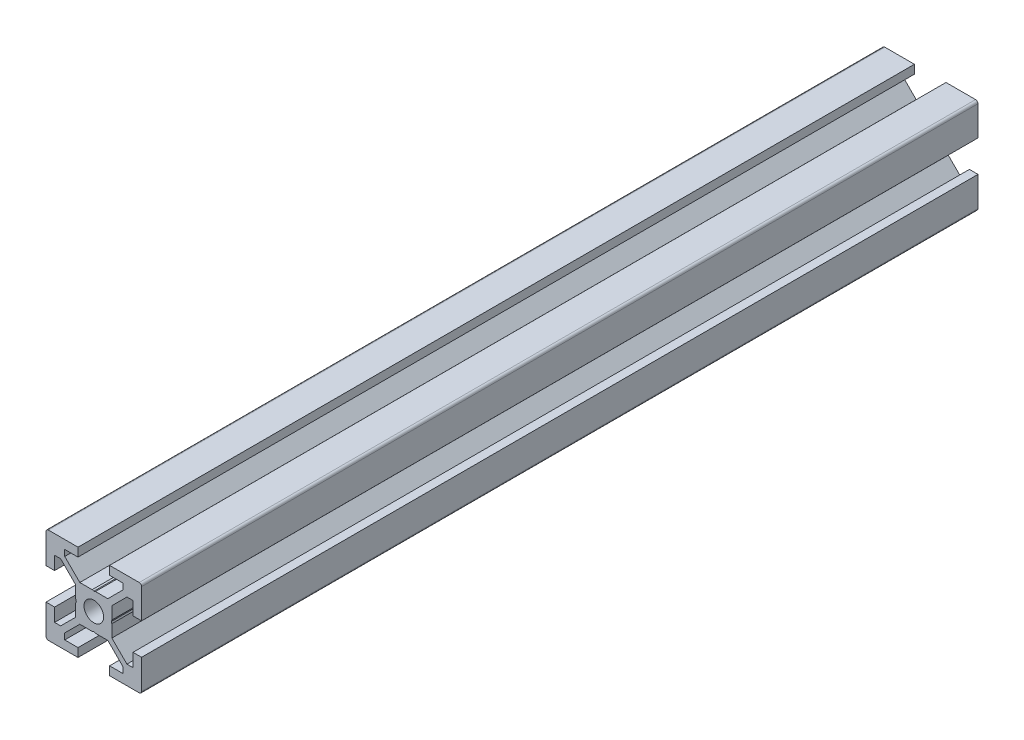
SolidWorks part; units mm, degrees
ref_plane "Front Plane" through (0, 0, 0) normal (0, 0, 1) x (1, 0, 0)
ref_plane "Top Plane" through (0, 0, 0) normal (0, 1, 0) x (1, 0, 0)
ref_plane "Right Plane" through (0, 0, 0) normal (1, 0, 0) x (0, 0, -1)
sketch "Sketch1" plane through (0, 0, 0) normal (0, 0, 1) x (1, 0, 0)
  line L0 (-3.3, 10) -> (-3.3, 8.2)
  line L1 (0, 0) -> (50000, 0) construction
  line L2 (-10, 3.3) -> (-10, 10)
  line L3 (-10, 10) -> (-3.3, 10)
  line L4 (0, 0) -> (0, 50000) construction
  line L5 (-10, -10) -> (10, 10) construction
  line L6 (-10, 10) -> (10, -10) construction
  line L7 (-2.9315, -3.78) -> (-0.34, -3.78)
  line L8 (-3.78, -2.9315) -> (-3.78, -0.34)
  line L9 (-2.9315, 3.78) -> (-0.34, 3.78)
  line L10 (3.78, -2.9315) -> (3.78, -0.34)
  line L11 (-3.78, -3.78) -> (3.78, 3.78) construction
  line L12 (-3.78, 3.78) -> (3.78, -3.78) construction
  line L13 (-6.08, 8.2) -> (-3.3, 8.2)
  line L14 (-8.2, 6.08) -> (-8.2, 3.3)
  line L15 (-8.2, 3.3) -> (-10, 3.3)
  line L16 (-8.2, 6.08) -> (-6.9285, 6.08)
  line L17 (-6.08, 8.2) -> (-6.08, 6.9285)
  line L18 (-6.9285, 6.08) -> (-3.78, 2.9315)
  line L19 (-6.08, 6.9285) -> (-2.9315, 3.78)
  line L20 (8.2, 6.08) -> (6.9285, 6.08)
  line L21 (8.2, 6.08) -> (8.2, 3.3)
  line L22 (8.2, 3.3) -> (10, 3.3)
  line L23 (10, 3.3) -> (10, 10)
  line L24 (10, 10) -> (3.3, 10)
  line L25 (3.3, 10) -> (3.3, 8.2)
  line L26 (6.08, 8.2) -> (3.3, 8.2)
  line L27 (6.08, 8.2) -> (6.08, 6.9285)
  line L28 (6.08, 6.9285) -> (2.9315, 3.78)
  line L29 (6.9285, 6.08) -> (3.78, 2.9315)
  line L30 (6.9285, -6.08) -> (3.78, -2.9315)
  line L31 (6.08, -6.9285) -> (2.9315, -3.78)
  line L32 (6.08, -8.2) -> (6.08, -6.9285)
  line L33 (6.08, -8.2) -> (3.3, -8.2)
  line L34 (3.3, -10) -> (3.3, -8.2)
  line L35 (10, -10) -> (3.3, -10)
  line L36 (10, -3.3) -> (10, -10)
  line L37 (8.2, -3.3) -> (10, -3.3)
  line L38 (8.2, -6.08) -> (8.2, -3.3)
  line L39 (8.2, -6.08) -> (6.9285, -6.08)
  line L40 (-6.08, -6.9285) -> (-2.9315, -3.78)
  line L41 (-6.9285, -6.08) -> (-3.78, -2.9315)
  line L42 (-6.08, -8.2) -> (-6.08, -6.9285)
  line L43 (-8.2, -6.08) -> (-6.9285, -6.08)
  line L44 (-8.2, -3.3) -> (-10, -3.3)
  line L45 (-8.2, -6.08) -> (-8.2, -3.3)
  line L46 (-6.08, -8.2) -> (-3.3, -8.2)
  line L47 (-10, -10) -> (-3.3, -10)
  line L48 (-10, -3.3) -> (-10, -10)
  line L49 (-3.3, -10) -> (-3.3, -8.2)
  line L50 (-0.34, 3.78) -> (0, 3.66)
  line L51 (0.34, 3.78) -> (0, 3.66)
  line L52 (0.34, 3.78) -> (2.9315, 3.78)
  line L53 (-3.78, -0.34) -> (-3.66, 0)
  line L54 (-3.78, 0.34) -> (-3.66, 0)
  line L55 (3.78, 0.34) -> (3.66, 0)
  line L56 (3.78, -0.34) -> (3.66, 0)
  line L57 (-0.34, -3.78) -> (0, -3.66)
  line L58 (0.34, -3.78) -> (0, -3.66)
  line L59 (3.78, 0.34) -> (3.78, 2.9315)
  line L60 (0.34, -3.78) -> (2.9315, -3.78)
  line L61 (-3.78, 0.34) -> (-3.78, 2.9315)
  circle A0 centre (0, 0) radius 2.05
  point P0 (0, 0)
  dimension "D3" = 4.1
  dimension "D1" = 20
  dimension "D2" = 20
  dimension "D4" = 7.56
  dimension "D5" = 6.7
  dimension "D6" = 6.7
  dimension "D7" = 0.6
  dimension "D8" = 3.92
  dimension "D9" = 0.34
  dimension "D10" = 0.12
extrude "Boss-Extrude1" add sketch "Sketch1" along normal blind 175
fillet "Fillet1" radius 0.5 4 edges at (-10, 10, 87.5) (-10, -10, 87.5) (10, -10, 87.5) (10, 10, 87.5)
